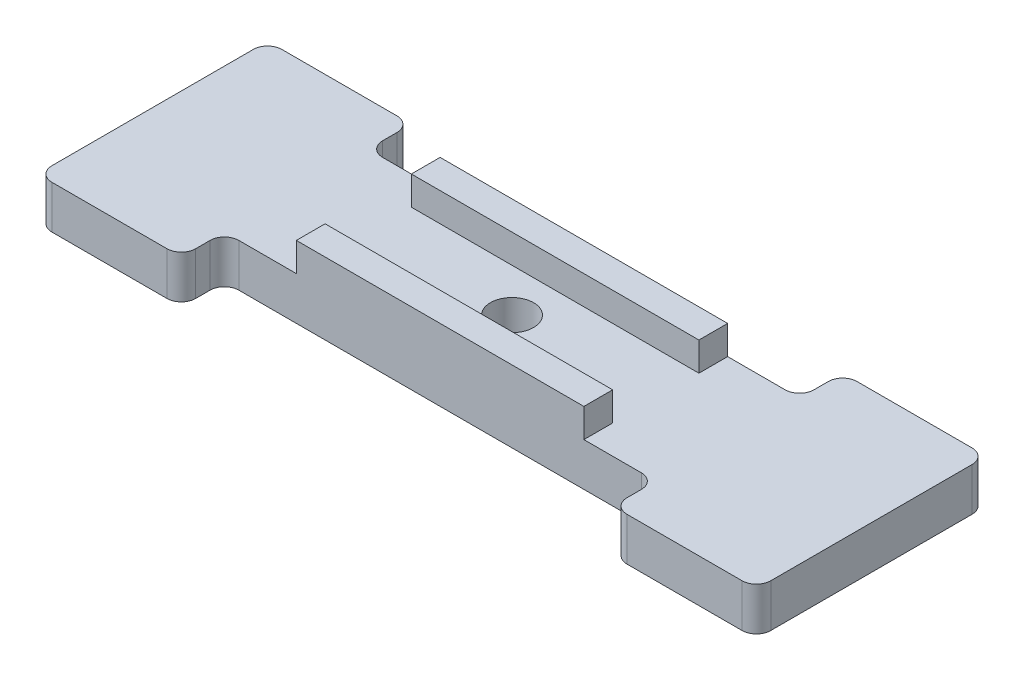
SolidWorks part; units mm, degrees
ref_plane "Front" through (0, 0, 0) normal (0, 0, 1) x (1, 0, 0)
ref_plane "Top" through (0, 0, 0) normal (0, 1, 0) x (1, 0, 0)
ref_plane "Right" through (0, 0, 0) normal (1, 0, 0) x (0, 0, -1)
sketch "Croquis1" plane through (0, 0, 0) normal (0, 1, 0) x (1, 0, 0)
  line L0 (-1000, 0) -> (49000, 0) construction
  line L1 (0, -1000) -> (0, 49000) construction
  line L2 (-15, -5) -> (15, -5)
  line L3 (-15, 5) -> (15, 5)
  line L4 (15, -8) -> (15, -5)
  line L5 (-15, -8) -> (-15, -5)
  line L6 (25, -8) -> (25, 8)
  line L7 (-25, -8) -> (-25, 8)
  line L8 (-25, -8) -> (-15, -8)
  line L9 (-25, 8) -> (-15, 8)
  line L10 (15, 8) -> (25, 8)
  line L11 (-25, -1000) -> (-25, 49000) construction
  line L12 (-15, -1000) -> (-15, 49000) construction
  line L13 (15, -8) -> (25, -8)
  line L14 (-1000, 8) -> (49000, 8) construction
  line L15 (-15, 5) -> (-15, 8)
  line L16 (-1000, -8) -> (49000, -8) construction
  line L17 (15, -1000) -> (15, 49000) construction
  line L18 (25, -1000) -> (25, 49000) construction
  line L19 (-1000, -5) -> (49000, -5) construction
  line L20 (-1000, 5) -> (49000, 5) construction
  line L21 (15, 5) -> (15, 8)
  circle A0 centre (0, 0) radius 1.5
  dimension "D9" = 3
  dimension "D1" = 5
  dimension "D2" = 5
  dimension "D3" = 15
  dimension "D4" = 15
  dimension "D5" = 25
  dimension "D6" = 25
  dimension "D7" = 8
  dimension "D8" = 8
extrude "Saliente-Extruir1" add sketch "Croquis1" along normal blind 3
sketch "Croquis2" plane through (0, 3, 0) normal (0, 1, 0) x (1, 0, 0)
  line L0 (15, 5) -> (-15, 5) construction
  line L1 (-10, 5) -> (10, 5)
  line L2 (-10, 5) -> (-10, 3)
  line L3 (-10, 3) -> (10, 3)
  line L4 (10, 5) -> (10, 3)
  line L5 (-1000, 0) -> (49000, 0) construction
  line L6 (0, -1000) -> (0, 49000) construction
  line L7 (-10, -5) -> (-10, -3)
  line L8 (-10, -3) -> (10, -3)
  line L9 (10, -5) -> (10, -3)
  line L10 (-10, -5) -> (10, -5)
  dimension "D1" = 10
  dimension "D2" = 10
  dimension "D3" = 2
extrude "Saliente-Extruir2" add sketch "Croquis2" along normal blind 2
fillet "Redondeo1" radius 1 12 edges at (-25, 1.5, -8) (-15, 1.5, -8) (-15, 1.5, -5) (15, 1.5, -5) (15, 1.5, -8) (25, 1.5, -8) (25, 1.5, 8) (15, 1.5, 8) (15, 1.5, 5) (-15, 1.5, 8) (-25, 1.5, 8) (-15, 1.5, 5)
